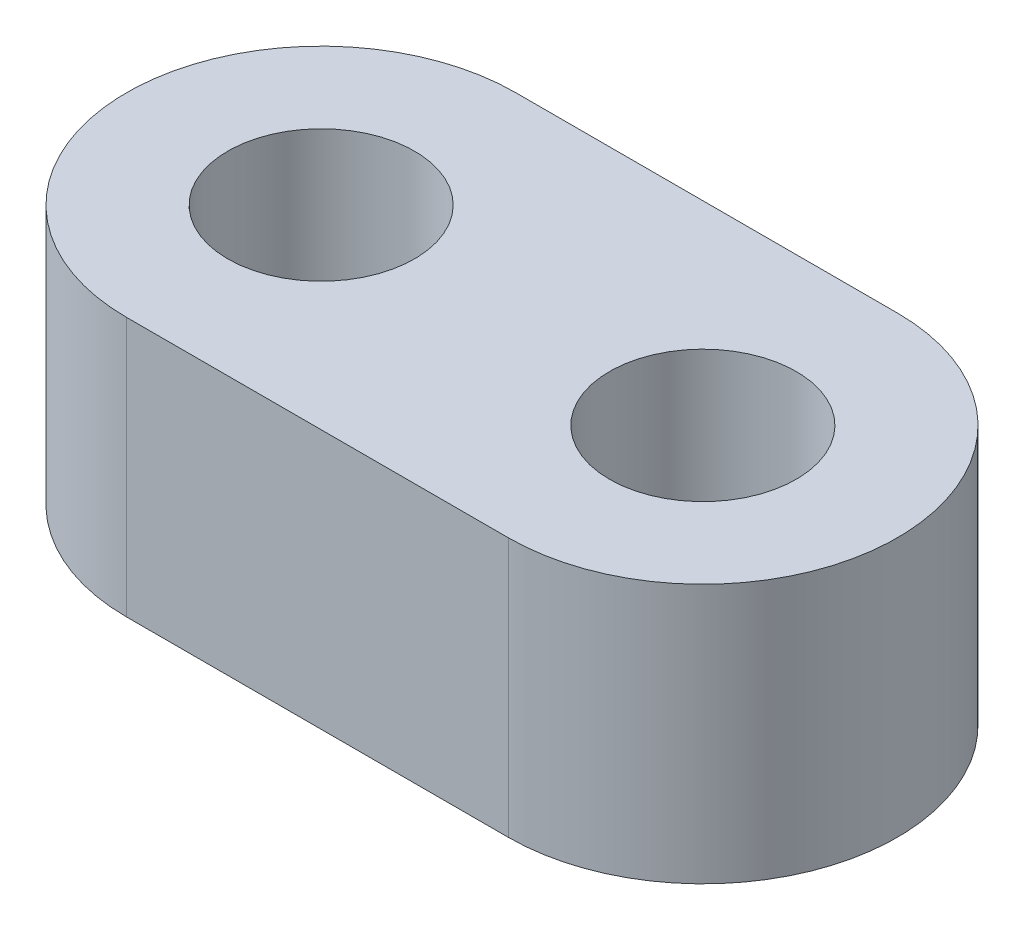
SolidWorks part; units mm, degrees
ref_plane "Front Plane" through (0, 0, 0) normal (0, 0, 1) x (1, 0, 0)
ref_plane "Top Plane" through (0, 0, 0) normal (0, 1, 0) x (1, 0, 0)
ref_plane "Right Plane" through (0, 0, 0) normal (1, 0, 0) x (0, 0, -1)
sketch "Sketch2" plane through (0, 0, 0) normal (0, 1, 0) x (1, 0, 0)
  line L0 (0, 4.7625) -> (14.1051, 4.7625)
  line L1 (14.1051, 4.7625) -> (14.1051, -4.7625)
  line L2 (14.1051, -4.7625) -> (0, -4.7625)
  arc A0 (0, 4.7625) -> (0, -4.7625) centre (0, 0) ccw
  circle A1 centre (0, 0) radius 2.286
  dimension "D1" = 4.572
  dimension "D2" = 4.7625
extrude "Boss-Extrude1" add sketch "Sketch2" along normal blind 6.35
sketch "Sketch3" plane through (14.1051, 0, 0) normal (1, 0, 0) x (0, 0, -1)
  circle A0 centre (0, 3.0961) radius 2.032
  dimension "D1" = 4.064
extrude "Cut-Extrude1" [suppressed] cut sketch "Sketch3" against normal blind 9.525
sketch "Sketch4" plane through (0, 6.35, 0) normal (0, 1, 0) x (1, 0, 0)
  line L0 (14.1051, -4.7625) -> (14.1051, 4.7625) construction
  line L1 (14.1051, 4.7625) -> (0, 4.7625) construction
  line L2 (0, -4.7625) -> (14.1051, -4.7625) construction
  line L3 (9.3426, 4.7625) -> (14.1051, 4.7625)
  line L4 (14.1051, 4.7625) -> (14.1051, -4.7625)
  line L5 (14.1051, -4.7625) -> (9.3426, -4.7625)
  circle A0 centre (9.3426, 0) radius 2.286
  circle A1 centre (0, 0) radius 2.286 construction
  arc A2 (9.3426, 4.7625) -> (9.3426, -4.7625) centre (9.3426, 0) cw
  point P7 (0, 0)
  point P8 (14.1051, 0)
  line M3 (0, -4.7625) -> (14.1051, -4.7625)
  line M4 (14.1051, -4.7625) -> (14.1051, 4.7625)
  line M5 (14.1051, 4.7625) -> (0, 4.7625)
  dimension "D1" = 4.7625
extrude "Cut-Extrude2" cut sketch "Sketch4" against normal through all contours A2 L4 M5 | A2 M4 M3 | A0
